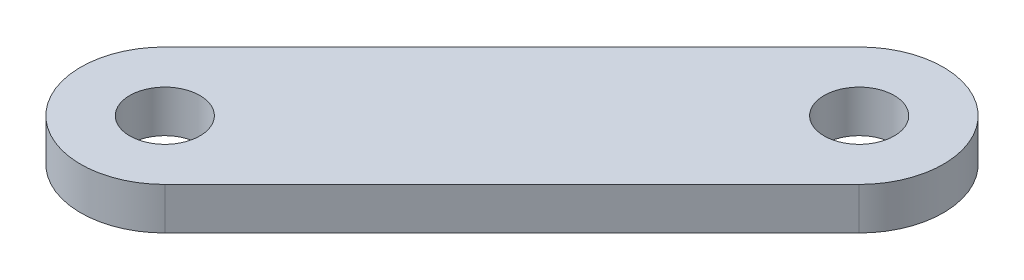
SolidWorks part; units mm, degrees
ref_plane "Plan de face" through (0, 0, 0) normal (0, 0, 1) x (1, 0, 0)
ref_plane "Plan de dessus" through (0, 0, 0) normal (0, 1, 0) x (1, 0, 0)
ref_plane "Plan de droite" through (0, 0, 0) normal (1, 0, 0) x (0, 0, -1)
sketch "Esquisse1" plane through (0, 39, 0) normal (0, 1, 0) x (1, 0, 0)
  line L0 (27.9309, -12.3383) -> (3.1822, -37.087)
  line L1 (36.4162, -20.8236) -> (11.6675, -45.5723)
  arc A0 (36.4162, -20.8236) -> (27.9309, -12.3383) centre (32.1736, -16.5809) ccw
  arc A1 (3.1822, -37.087) -> (11.6675, -45.5723) centre (7.4248, -41.3297) ccw
  circle A2 centre (32.1736, -16.5809) radius 2.5
  circle A3 centre (32.1736, -16.5809) radius 2.5 construction
  circle A4 centre (7.4248, -41.3297) radius 2.5
  dimension "D1" = 12
extrude "Boss.-Extru.1" add sketch "Esquisse1" along normal blind 3
